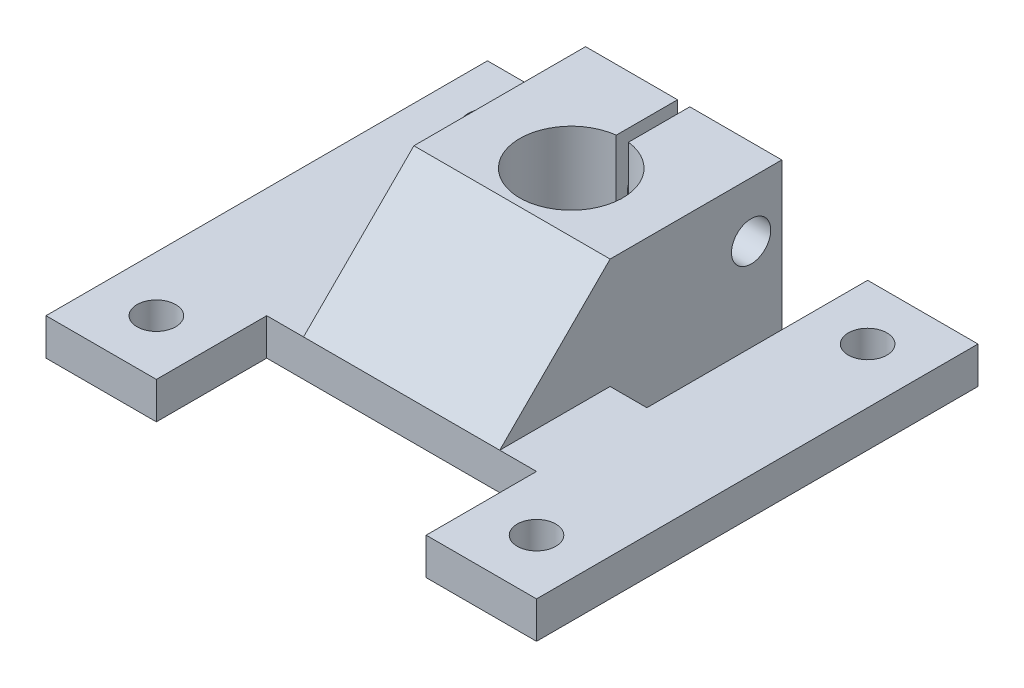
SolidWorks part; units mm, degrees
ref_plane "Front Plane" through (0, 0, 0) normal (0, 0, 1) x (1, 0, 0)
ref_plane "Top Plane" through (0, 0, 0) normal (0, 1, 0) x (1, 0, 0)
ref_plane "Right Plane" through (0, 0, 0) normal (1, 0, 0) x (0, 0, -1)
sketch "Sketch2" plane through (0, 0, 0) normal (0, 1, 0) x (1, 0, 0)
  line L0 (0, 0) -> (9, 0)
  line L1 (9, 0) -> (9, -18)
  line L2 (12, -18) -> (9, -18)
  line L3 (31, -18) -> (31, 0)
  line L4 (31, 0) -> (40, 0)
  line L5 (40, 0) -> (40, -36)
  line L6 (40, -36) -> (31, -36)
  line L7 (31, -36) -> (31, -27)
  line L8 (31, -27) -> (9, -27)
  line L9 (9, -27) -> (9, -36)
  line L10 (9, -36) -> (0, -36)
  line L11 (0, -36) -> (0, 0)
  line L12 (12, -4) -> (12, -18)
  line L13 (12, -4) -> (19.5, -4)
  line L14 (19.5, -4) -> (19.5, -9)
  line L15 (20.5, -9) -> (20.5, -4)
  line L16 (20.5, -4) -> (28, -4)
  line L17 (28, -4) -> (28, -18)
  line L18 (28, -18) -> (31, -18)
  line L19 (12, -18) -> (28, -18)
  line L20 (20, -1027) -> (20, 48973) construction
  arc A0 (19.5, -9) -> (20.5, -9) centre (20, -13.1701) ccw
  circle A1 centre (4.5, -4.5) radius 1.575
  circle A2 centre (4.5, -31.5) radius 1.575
  circle A3 centre (35.5, -31.5) radius 1.575
  circle A4 centre (35.5, -4.5) radius 1.575
  point P25 (20, -27)
  point P30 (4.5, -36)
  point P31 (9, -31.5)
  point P32 (4.5, 0)
  dimension "D7" = 4.2
  dimension "D13" = 3
  dimension "D17" = 3.15
  dimension "D18" = 3.15
  dimension "D1" = 9
  dimension "D2" = 18
  dimension "D3" = 9
  dimension "D4" = 9
  dimension "D5" = 9
  dimension "D6" = 9
  dimension "D8" = 7.5
  dimension "D9" = 7.5
  dimension "D10" = 5
  dimension "D11" = 5
  dimension "D12" = 14
  dimension "D14" = 3
  dimension "D15" = 36
  dimension "D16" = 1
  dimension "D19" = 4.5
  dimension "D20" = 4.5
  dimension "D21" = 4.5
  dimension "D22" = 4.5
extrude "Boss-Extrude4" add sketch "Sketch2" along normal blind 3 contours L20 L8 L7 L6 L5 L4 L3 L18 L19 A3 A4 | L8 L20 L19 L2 L1 L0 L11 L10 L9 A1 A2 | L20 L19 L17 L16 L15 A0 | L19 L20 A0 L14 L13 L12
sketch "Sketch6" plane through (0, 3, 0) normal (0, 1, 0) x (1, 0, 0)
  line L0 (12, -18) -> (28, -18) construction
  arc M1 (20.5, -9) -> (19.5, -9) centre (20, -13.1701) cw
  line M2 (19.5, -9) -> (19.5, -4)
  line M3 (19.5, -4) -> (12, -4)
  line M4 (12, -4) -> (12, -18)
  line M18 (28, -18) -> (28, -4)
  line M19 (28, -4) -> (20.5, -4)
  line M20 (20.5, -4) -> (20.5, -9)
extrude "Boss-Extrude5" add sketch "Sketch6" along normal blind 9 contours L0 M4 M18 M19 M20 M1 M2 M3
ref_plane "Plane2" through (20, 0, 0) normal (-1, 0, 0) x (0, 0, 1)
sketch "Sketch8" plane through (20, 0, 0) normal (-1, 0, 0) x (0, 0, 1)
  line L2 (18, 12) -> (27, 3)
rib "Rib2" sketch "Sketch8" sketch "Sketch8" thickness 16 extrusion direction parallel to sketch draft on no parameters "D1"=16
sketch "Sketch9" plane through (12, 0, 0) normal (-1, 0, 0) x (0, 0, 1)
  line L0 (4, 12) -> (4, 0) construction
  line L2 (4, 12) -> (18, 12) construction
  circle A0 centre (6.5, 7.5) radius 1.6
  dimension "D1" = 3.2
  dimension "D2" = 2.5
  dimension "D3" = 4.5
extrude "Cut-Extrude1" cut sketch "Sketch9" against normal through all
